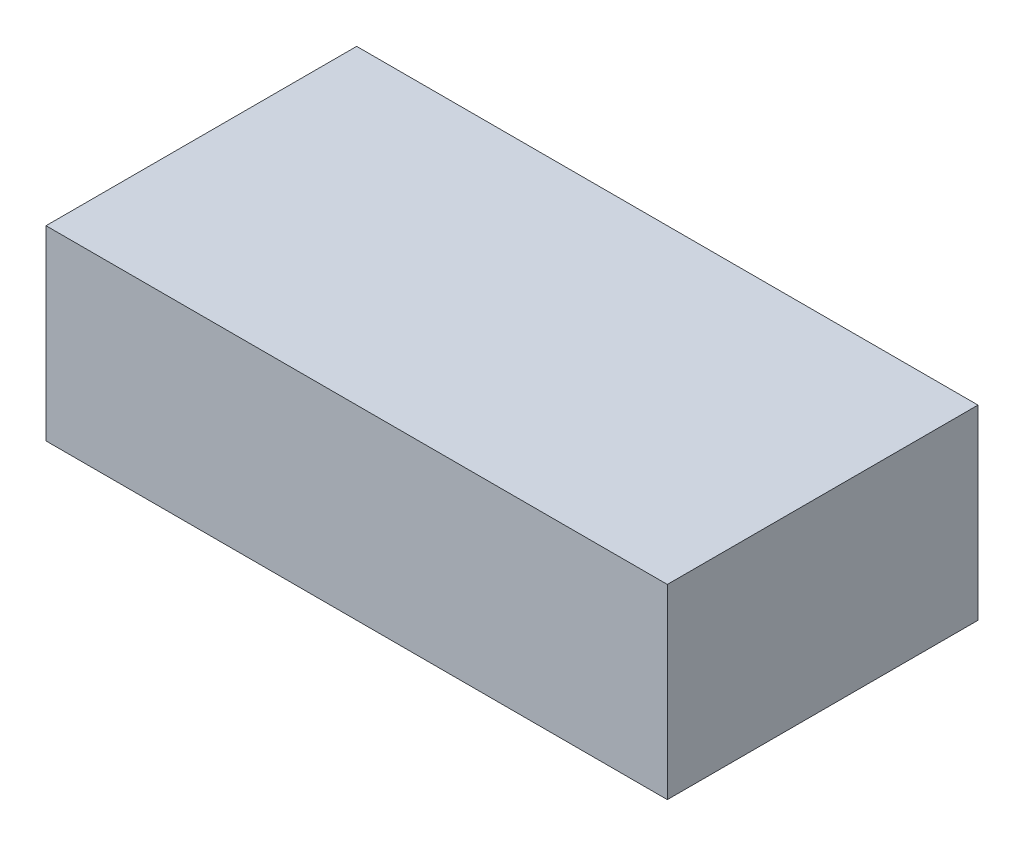
SolidWorks part; units mm, degrees
ref_plane "前视基准面" through (0, 0, 0) normal (0, 0, 1) x (1, 0, 0)
ref_plane "上视基准面" through (0, 0, 0) normal (0, 1, 0) x (1, 0, 0)
ref_plane "右视基准面" through (0, 0, 0) normal (1, 0, 0) x (0, 0, -1)
sketch "草图1" plane through (0, 0, 0) normal (0, 1, 0) x (1, 0, 0)
  line L0 (-100, 50) -> (100, 50)
  line L1 (-100, 50) -> (-100, -50)
  line L2 (-100, -50) -> (100, -50)
  line L3 (100, 50) -> (100, -50)
  line L4 (-100, 50) -> (100, -50) construction
  line L5 (-100, -50) -> (100, 50) construction
  point P0 (0, 0)
  dimension "D1" = 200
  dimension "D2" = 100
extrude "凸台-拉伸1" add sketch "草图1" along normal blind 60 contours L0 L3 L2 L1
